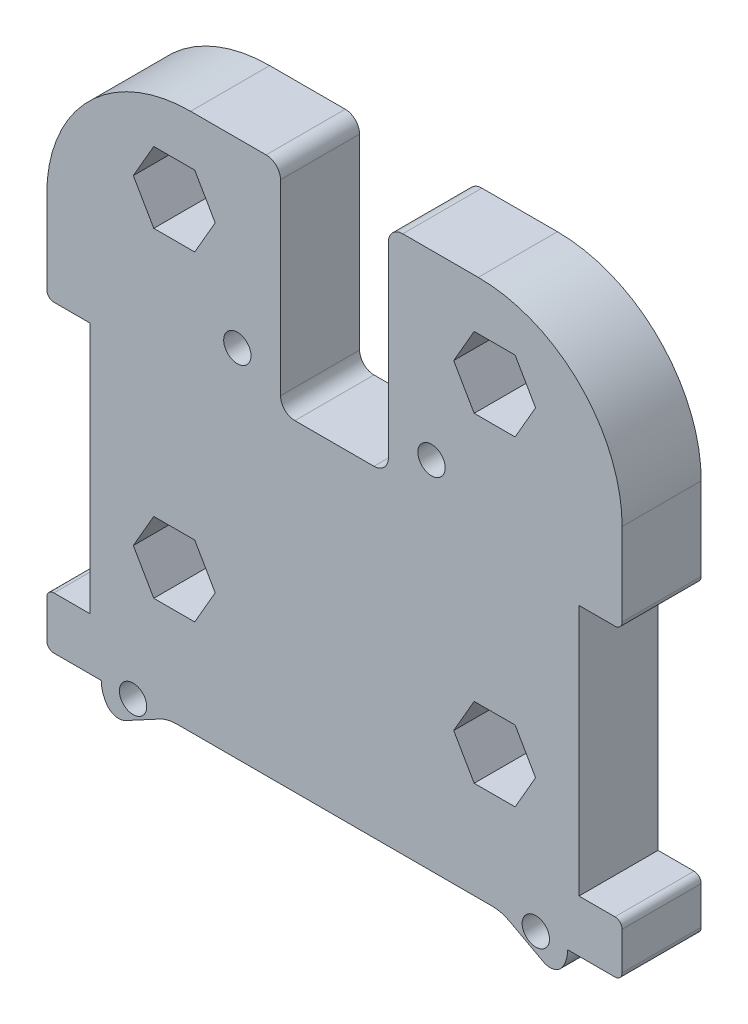
SolidWorks part; units mm, degrees
ref_plane "前视基准面" through (0, 0, 0) normal (0, 0, 1) x (1, 0, 0)
ref_plane "上视基准面" through (0, 0, 0) normal (0, 1, 0) x (1, 0, 0)
ref_plane "右视基准面" through (0, 0, 0) normal (1, 0, 0) x (0, 0, -1)
sketch "草图1" plane through (0, 0, 0) normal (0, 0, 1) x (1, 0, 0)
  line L0 (0, 0) -> (0, 36.8895) construction
  line L2 (-40, 50) -> (40, 50)
  line L3 (-40, 50) -> (-40, -50)
  line L4 (-40, -50) -> (40, -50)
  line L5 (40, 50) -> (40, -50)
  dimension "D1" = 80
  dimension "D2" = 100
  dimension "D3" = 40
  dimension "D4" = 50
extrude "凸台-拉伸1" add sketch "草图1" along normal blind 11 contours L2 L5 L4 L3
sketch "草图7" plane through (0, 0, 11) normal (0, 0, 1) x (1, 0, 0)
  line L0 (0, 0) -> (0, 50) construction
  line L1 (-40, 50) -> (40, 50) construction
  line L3 (-7.5, 50) -> (7.5, 50)
  line L4 (-7.5, 50) -> (-7.5, 20)
  line L5 (-7.5, 20) -> (7.5, 20)
  line L6 (7.5, 50) -> (7.5, 20)
  dimension "D1" = 30
  dimension "D2" = 15
  dimension "D3" = 7.5
extrude "切除-拉伸1" cut sketch "草图7" against normal blind 16
sketch "草图2" plane through (0, 0, 11) normal (0, 0, 1) x (1, 0, 0)
  line L0 (0, 0) -> (0, -50) construction
  line L1 (-40, -50) -> (40, -50) construction
  line L2 (-23.6474, -14.5) -> (32.5152, -14.5) construction
  line L3 (-25.0117, -34.5) -> (44.0357, -34.5) construction
  line L4 (-19.0329, -14.5) -> (-17.8955, -14.5)
  line L5 (17.8955, -14.5) -> (19.0329, -14.5)
  line L6 (17.8955, -34.5) -> (19.0329, -34.5)
  line L7 (-19.0329, -34.5) -> (-17.8955, -34.5)
  arc A0 (-17.8955, -14.5) -> (-17.8955, -34.5) centre (0, -24.5) ccw
  arc A1 (-19.0329, -14.5) -> (-19.0329, -34.5) centre (0, -24.5) ccw
  arc A2 (17.8955, -34.5) -> (17.8955, -14.5) centre (0, -24.5) ccw
  arc A3 (19.0329, -34.5) -> (19.0329, -14.5) centre (0, -24.5) ccw
  dimension "D1" = 25.5
  dimension "D2" = 10
  dimension "D4" = 21.5
  dimension "D5" = 20.5
  dimension "D3" = 20
sketch "草图5" plane through (0, 0, 0) normal (0, 0, -1) x (-1, 0, 0)
  line L0 (0, 30) -> (0, -50) construction
  line L2 (40, -50) -> (-40, -50) construction
  point P6 (-13.5, 24.75)
  point P7 (-28, -24.75)
  point P8 (28, -24.75)
  point P9 (13.5, 24.75)
  dimension "D1" = 13.5
  dimension "D2" = 28
  dimension "D3" = 49.5
  dimension "D4" = 24.75
hole_wizard "M4 螺纹孔1" positions "3D草图2" profile "草图6" tap size "M4" standard "GB" end condition up to next
sketch3d "3D草图2"
  point P0 (13.5, 24.75, 0)
  point P3 (-13.5, 24.75, 0)
  point P6 (-28, -24.75, 0)
  point P9 (28, -24.75, 0)
sketch "草图6" plane through (13.5, 24.75, 0) normal (1, 0, 0) x (0, 1, 0)
  line L0 (0, 0) -> (0, 11)
  line L1 (0, 11) -> (1.65, 11)
  line L2 (1.65, 11) -> (1.65, 0.375)
  line L3 (1.65, 0.375) -> (2.025, 0)
  line L5 (2.025, 0) -> (0, 0)
  line L6 (-1.65, 0.375) -> (-2.025, 0) construction
  line L11 (0, -6.35) -> (0, 107.95) construction
  dimension "通孔螺纹孔钻头直径" = 3.3
  dimension "通孔螺纹孔钻头深度" = 11
  dimension "近端锥形沉头孔直径" = 4.05
  dimension "近端锥形沉头孔角度" = 90
cosmetic thread "孔螺蚊线1" parameters "D2"=4
cosmetic thread "孔螺蚊线2" parameters "D2"=4
cosmetic thread "孔螺蚊线3" parameters "D2"=4
cosmetic thread "孔螺蚊线4" parameters "D2"=4
fillet "圆角1" radius 20 2 edges at (40, 50, 5.5) (-40, 50, 5.5)
fillet "圆角2" radius 2 6 edges at (40, -50, 5.5) (-40, -50, 5.5) (-7.5, 50, 5.5) (-7.5, 20, 5.5) (7.5, 20, 5.5) (7.5, 50, 5.5)
sketch "草图9" plane through (0, 0, 0) normal (0, 0, 1) x (1, 0, 0)
  line L0 (40, 17.5) -> (34, 17.5)
  line L1 (40, 30) -> (40, -48) construction
  line L2 (34, 17.5) -> (34, -17.5)
  line L3 (40, 17.5) -> (40, -17.5)
  line L4 (0, 0) -> (46.0009, 0) construction
  line L5 (40, -17.5) -> (34, -17.5)
  line L6 (0, 0) -> (0, 43.2165) construction
  line L7 (-40, -17.5) -> (-34, -17.5)
  line L8 (-34, 17.5) -> (-34, -17.5)
  line L9 (-40, 17.5) -> (-34, 17.5)
  line L10 (-40, 17.5) -> (-40, -17.5)
  point P12 (34, 0)
  dimension "D1" = 35
  dimension "D2" = 6
extrude "切除-拉伸2" cut sketch "草图9" along normal blind 11
sketch "草图11" plane through (0, 0, 0) normal (0, 0, 1) x (1, 0, 0)
  line L0 (0, 36.6897) -> (0, -57.9108) construction
  line L1 (0, 30) -> (0, -50) construction
  line L2 (0, 16) -> (-52.3712, 16) construction
  line L3 (0, 16) -> (-36.4685, 52.4685) construction
  circle A0 centre (0, 16) radius 31.5 construction
  circle A1 centre (-22.2739, 38.2739) radius 3
  circle A2 centre (22.2739, 38.2739) radius 3
  circle A3 centre (22.2739, -6.2739) radius 3
  circle A4 centre (-22.2739, -6.2739) radius 3
  point P20 (0, 16)
  dimension "D1" = 63
  dimension "D4" = 6
  dimension "D2" = 16
  dimension "D3" = 45
  dimension "D5" = 4
extrude "切除-拉伸4" cut sketch "草图11" along normal blind 15
sketch "草图12" plane through (0, 0, 0) normal (0, 0, 1) x (1, 0, 0)
  line L0 (0, 41.1031) -> (0, -79.5039) construction
  circle A4 centre (13.5, 24.75) radius 3.43
  circle A5 centre (28, -24.75) radius 3.43
  circle A6 centre (-28, -24.75) radius 3.43
  circle A7 centre (-13.5, 24.75) radius 3.43
  dimension "D1" = 6.86
  dimension "D2" = 6.86
extrude "切除-拉伸5" cut sketch "草图12" along normal blind 3.9
sketch "草图13" plane through (0, 0, 11) normal (0, 0, 1) x (1, 0, 0)
  line L0 (0, 30) -> (0, -54.2815) construction
  line L1 (-19.4275, 33.3439) -> (-16.5812, 38.2739)
  line L2 (-16.5812, 38.2739) -> (-19.4275, 43.2039)
  line L3 (-19.4275, 43.2039) -> (-25.1202, 43.2039)
  line L4 (-25.1202, 43.2039) -> (-27.9665, 38.2739)
  line L5 (-27.9665, 38.2739) -> (-25.1202, 33.3439)
  line L6 (-25.1202, 33.3439) -> (-19.4275, 33.3439)
  line L7 (-19.4275, -11.2039) -> (-16.5812, -6.2739)
  line L8 (-16.5812, -6.2739) -> (-19.4275, -1.3439)
  line L9 (-19.4275, -1.3439) -> (-25.1202, -1.3439)
  line L10 (-25.1202, -1.3439) -> (-27.9665, -6.2739)
  line L11 (-27.9665, -6.2739) -> (-25.1202, -11.2039)
  line L12 (-25.1202, -11.2039) -> (-19.4275, -11.2039)
  line L13 (25.1202, -11.2039) -> (19.4275, -11.2039)
  line L14 (27.9665, -6.2739) -> (25.1202, -11.2039)
  line L15 (25.1202, -1.3439) -> (27.9665, -6.2739)
  line L16 (19.4275, -1.3439) -> (25.1202, -1.3439)
  line L17 (16.5812, -6.2739) -> (19.4275, -1.3439)
  line L18 (19.4275, -11.2039) -> (16.5812, -6.2739)
  line L19 (25.1202, 33.3439) -> (19.4275, 33.3439)
  line L20 (27.9665, 38.2739) -> (25.1202, 33.3439)
  line L21 (25.1202, 43.2039) -> (27.9665, 38.2739)
  line L22 (19.4275, 43.2039) -> (25.1202, 43.2039)
  line L23 (16.5812, 38.2739) -> (19.4275, 43.2039)
  line L24 (19.4275, 33.3439) -> (16.5812, 38.2739)
  circle A0 centre (-22.2739, 38.2739) radius 4.93 construction
  circle A1 centre (-22.2739, -6.2739) radius 4.93 construction
  circle A2 centre (22.2739, -6.2739) radius 4.93 construction
  circle A3 centre (22.2739, 38.2739) radius 4.93 construction
  dimension "D1" = 9.86
  dimension "D2" = 9.86
extrude "切除-拉伸6" cut sketch "草图13" against normal blind 8.5
sketch "草图14" plane through (0, 0, 0) normal (0, 0, -1) x (-1, 0, 0)
  line L0 (-28, -24.75) -> (52.474, -24.75) construction
  line L1 (0, 0) -> (0, -65.5575) construction
  line L2 (-42.2815, -24.75) -> (-32.43, -24.75)
  line L3 (-42.2815, -24.75) -> (-42.2815, -58.5485)
  line L4 (-42.2815, -58.5485) -> (45.7714, -58.5485)
  line L5 (45.7714, -24.75) -> (45.7714, -58.5485)
  line L6 (-21.948, -24.75) -> (21.948, -24.75)
  line L7 (32.43, -24.75) -> (45.7714, -24.75)
  line L8 (-24.315, -25.3458) -> (-29.053, -27.8922)
  line L9 (24.315, -25.3458) -> (29.053, -27.8922)
  arc A0 (-32.43, -24.75) -> (-31.6457, -27.2666) centre (-28, -24.75) ccw
  circle A1 centre (-28, -24.75) radius 3.43 construction
  arc A2 (32.43, -24.75) -> (31.6457, -27.2666) centre (28, -24.75) cw
  arc A3 (-31.6457, -27.2666) -> (-29.053, -27.8922) centre (-29.9998, -26.1305) ccw
  arc A4 (-21.948, -24.75) -> (-24.315, -25.3458) centre (-21.948, -29.75) ccw
  arc A5 (21.948, -24.75) -> (24.315, -25.3458) centre (21.948, -29.75) cw
  arc A6 (31.6457, -27.2666) -> (29.053, -27.8922) centre (29.9998, -26.1305) cw
  point P22 (-30.277, -28.55)
  point P25 (-23.2065, -24.75)
  dimension "D1" = 1
  dimension "D3" = 2
  dimension "D4" = 5
  dimension "D2" = 3.8
extrude "切除-拉伸7" cut sketch "草图14" against normal blind 14
sketch "草图15" plane through (0, 0, 11) normal (0, 0, 1) x (1, 0, 0)
  line L0 (0, 0) -> (0, 55.0159) construction
  circle A0 centre (-13.5, 24.75) radius 1.9
  circle A1 centre (-28, -24.75) radius 1.9
  circle A2 centre (13.5, 24.75) radius 1.9
  circle A3 centre (28, -24.75) radius 1.9
  dimension "D1" = 3.8
  dimension "D2" = 3.8
extrude "切除-拉伸8" cut sketch "草图15" against normal blind 14
fillet "圆角4" radius 0.12 4 edges at (-29.1996, -27.9634, 1.95) (-24.6602, -25.5313, 1.95) (24.6602, -25.5313, 1.95) (29.1996, -27.9634, 1.95)
fillet "圆角5" radius 1 6 edges at (-40, 17.5, 5.5) (-40, -17.5, 5.5) (-40, -24.75, 5.5) (40, -24.75, 5.5) (40, -17.5, 5.5) (40, 17.5, 5.5)
